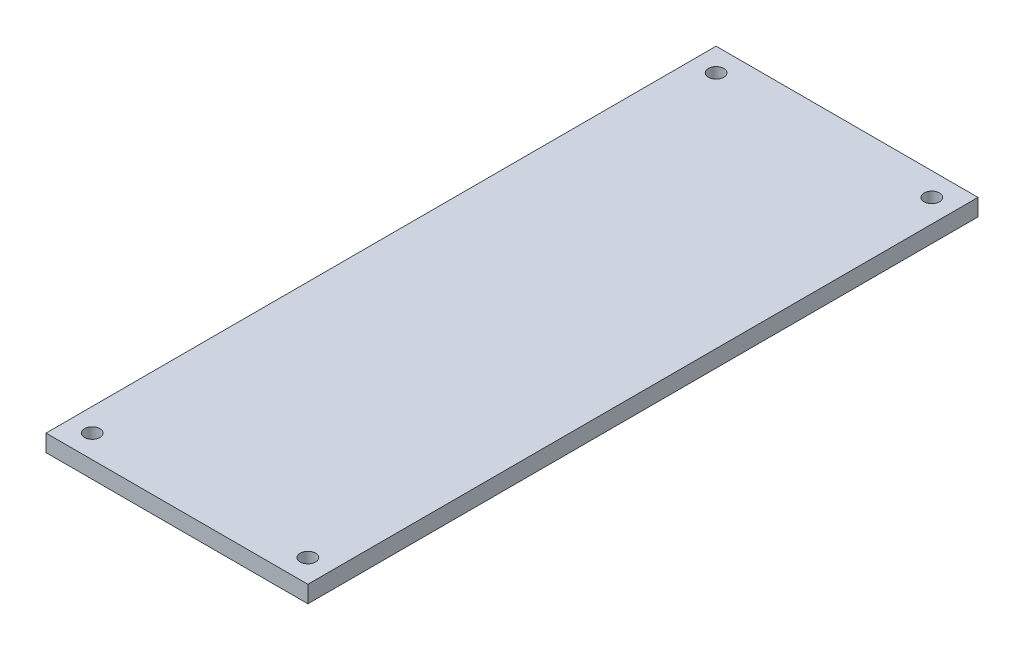
SolidWorks part; units mm, degrees
ref_plane "前视基准面" through (0, 0, 0) normal (0, 0, 1) x (1, 0, 0)
ref_plane "上视基准面" through (0, 0, 0) normal (0, 1, 0) x (1, 0, 0)
ref_plane "右视基准面" through (0, 0, 0) normal (1, 0, 0) x (0, 0, -1)
other "Configuration Table"
sketch "草图1" plane through (0, 0, 0) normal (0, 1, 0) x (1, 0, 0)
  line L1 (0, 0) -> (34, 0)
  line L2 (0, 0) -> (0, -87)
  line L3 (0, -87) -> (34, -87)
  line L4 (34, 0) -> (34, -87)
  circle A2 centre (3, -3) radius 1
  circle A3 centre (31, -3) radius 1
  circle A4 centre (31, -84) radius 1
  circle A5 centre (3, -84) radius 1
  point P13 (0, 0)
  point P14 (0, 0)
  point P15 (0, 0)
  point P16 (0, 0)
  dimension "D3" = 3
  dimension "D6" = 3
  dimension "D7" = 2
  dimension "D1" = 87
  dimension "D2" = 34
  dimension "D4" = 3
  dimension "D5" = 3
extrude "凸台-拉伸1" add sketch "草图1" along normal blind 2.2
